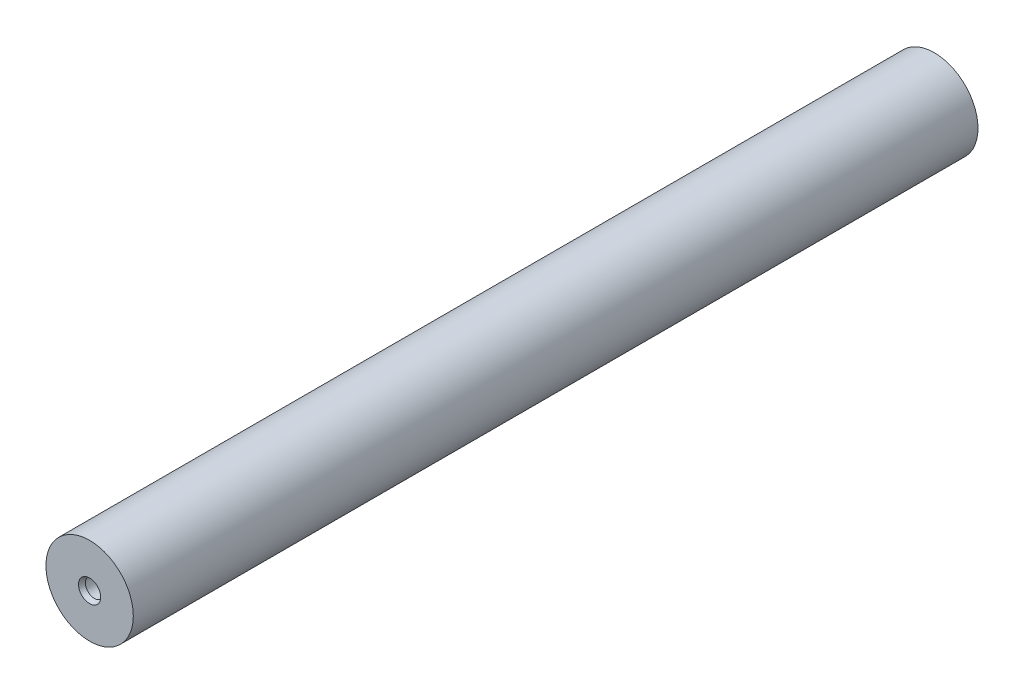
SolidWorks part; units mm, degrees
ref_plane "前基準面" through (0, 0, 0) normal (0, 0, 1) x (1, 0, 0)
ref_plane "上基準面" through (0, 0, 0) normal (0, 1, 0) x (1, 0, 0)
ref_plane "右基準面" through (0, 0, 0) normal (1, 0, 0) x (0, 0, -1)
sketch "草圖1" plane through (0, 0, 0) normal (0, 0, 1) x (1, 0, 0)
  circle A0 centre (0, 0) radius 6
  dimension "D1" = 12
extrude "填料-伸長1" add sketch "草圖1" along normal blind 116
ref_plane "平面1" through (0, 0, 116) normal (0, 0, -1) x (-1, 0, 0)
sketch "草圖5" plane through (0, 0, 116) normal (0, 0, -1) x (-1, 0, 0)
  circle A0 centre (0, 0) radius 1.3
  dimension "D1" = 2.6
hole_wizard "M3 螺紋孔3" positions "3D草圖3" profile "草圖6" tap size "M3" standard "ISO"
sketch3d "3D草圖3"
  point P0 (0, 0, 116)
  point P3 (0, 0, 116)
sketch "草圖6" plane through (0, 0, 116) normal (1, 0, 0) x (0, -1, 0)
  line L0 (0, 0) -> (0, 7.5)
  line L1 (0, 7.5) -> (1.25, 6.7489)
  line L2 (1.25, 6.7489) -> (1.25, 0.6639)
  line L3 (1.25, 0.6639) -> (1.525, 0)
  line L5 (1.525, 0) -> (0, 0)
  line L6 (-1.25, 0.6639) -> (-1.525, 0) construction
  line L10 (0, 7.5) -> (-1.25, 6.7489) construction
  line L11 (0, -6.35) -> (0, 107.95) construction
  dimension "螺孔鑽直徑" = 2.5
  dimension "螺孔鑽深度" = 7.5
  dimension "近端錐孔直徑" = 3.05
  dimension "近端錐孔角度" = 45
  dimension "導頭角度" = 118
hole_wizard "M3 螺紋孔4" positions "3D草圖4" profile "草圖7" tap size "M3" standard "ISO"
sketch3d "3D草圖4"
  point P0 (0, 0, 0)
  point P3 (0, 0, 0)
sketch "草圖7" plane through (0, 0, 0) normal (1, 0, 0) x (0, 1, 0)
  line L0 (0, 0) -> (0, 7.5)
  line L1 (0, 7.5) -> (1.25, 6.7489)
  line L2 (1.25, 6.7489) -> (1.25, 0.6639)
  line L3 (1.25, 0.6639) -> (1.525, 0)
  line L5 (1.525, 0) -> (0, 0)
  line L6 (-1.25, 0.6639) -> (-1.525, 0) construction
  line L10 (0, 7.5) -> (-1.25, 6.7489) construction
  line L11 (0, -6.35) -> (0, 107.95) construction
  dimension "螺孔鑽直徑" = 2.5
  dimension "螺孔鑽深度" = 7.5
  dimension "近端錐孔直徑" = 3.05
  dimension "近端錐孔角度" = 45
  dimension "導頭角度" = 118
